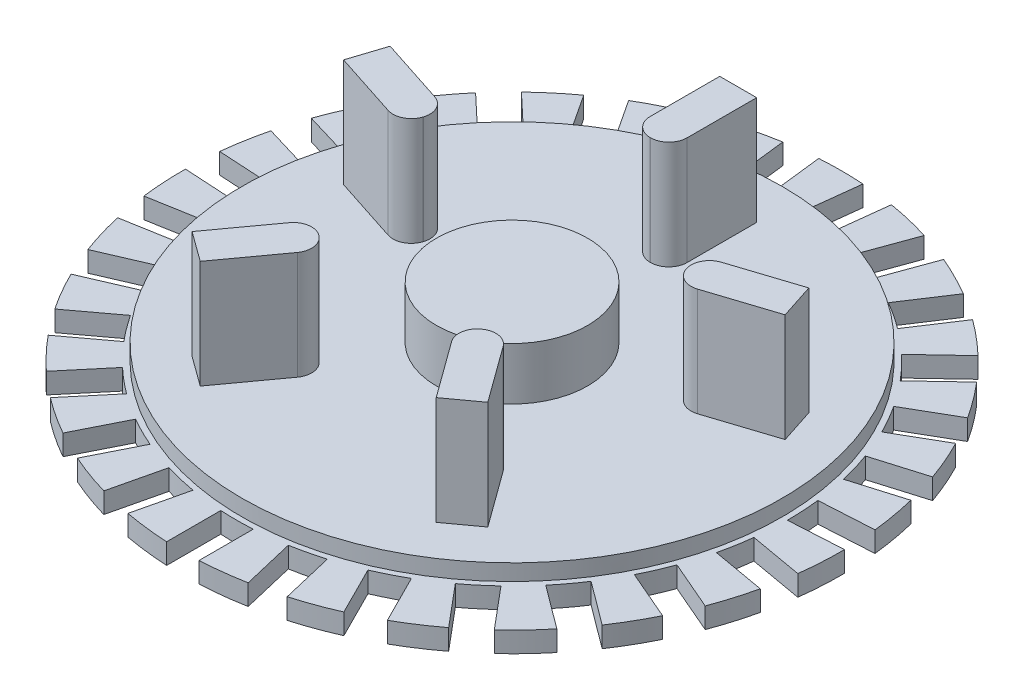
SolidWorks part; units mm, degrees
ref_plane "Front Plane" through (0, 0, 0) normal (0, 0, 1) x (1, 0, 0)
ref_plane "Top Plane" through (0, 0, 0) normal (0, 1, 0) x (1, 0, 0)
ref_plane "Right Plane" through (0, 0, 0) normal (1, 0, 0) x (0, 0, -1)
sketch "Sketch1" plane through (0, 0, 0) normal (0, 1, 0) x (1, 0, 0)
  circle A0 centre (0, 0) radius 25
  dimension "D1" = 50
extrude "Boss-Extrude1" add sketch "Sketch1" along normal blind 1.5
sketch "Sketch2" plane through (0, 1.5, 0) normal (0, 1, 0) x (1, 0, 0)
  line L0 (-1.7088, 14.5) -> (-1.7088, 19.3)
  line L1 (-0.0088, 12.8) -> (0.0088, 12.8)
  line L2 (-1.7088, 20.9304) -> (1.7088, 12.8) construction
  line L3 (1.7088, 14.5) -> (1.7088, 19.3)
  line L4 (-1.7088, 12.8) -> (1.7088, 20.9304) construction
  line L5 (0, -0.825) -> (0, 0.825) construction
  line L6 (-1.7088, 19.3) -> (-1.7088, 20.9304)
  line L7 (-1.7088, 20.9304) -> (1.7088, 20.9304)
  line L8 (1.7088, 20.9304) -> (1.7088, 19.3)
  arc A0 (0.0096, 21) -> (-0.0096, 21) centre (0, 0) ccw construction
  arc A1 (-1.7088, 19.3) -> (-0.0096, 21) centre (-0.0088, 19.3) cw construction
  arc A2 (1.7088, 19.3) -> (0.0096, 21) centre (0.0088, 19.3) ccw construction
  arc A3 (1.7088, 14.5) -> (0.0088, 12.8) centre (0.0088, 14.5) cw
  arc A4 (-1.7088, 14.5) -> (-0.0088, 12.8) centre (-0.0088, 14.5) ccw
  point P1 (0, 16.8652)
  point P3 (0, 21)
  dimension "D1" = 42
  dimension "D2" = 1.7
  dimension "D4" = 1.7
  dimension "D6" = 1.7
  dimension "D3" = 3.4176
  dimension "D5" = 6.5
extrude "Boss-Extrude2" add sketch "Sketch2" along normal blind 10
pattern_circular "CirPattern1" count 5 over 360 about axis through (0, 0, 0) along (0, 1, 0) of "Boss-Extrude2"
sketch "Sketch3" plane through (0, 0, 0) normal (0, -1, 0) x (1, 0, 0)
  circle A0 centre (0, 0) radius 30.5
  dimension "D1" = 61
extrude "Boss-Extrude3" add sketch "Sketch3" along normal blind 1.9
sketch "Sketch4" plane through (0, -1.9, 0) normal (0, -1, 0) x (1, 0, 0)
  line L0 (-1.5, 30.9637) -> (-1.5, 25.4558)
  line L1 (5.6812, 30.475) -> (4.411, 25.1156)
  line L2 (8.6003, 29.7831) -> (7.3301, 24.4238)
  line L3 (1.5, 30.9637) -> (1.5, 25.4558)
  line L4 (-1.4809, 30.9646) -> (1.5, 25.4558) construction
  line L5 (-1.5, 25.4558) -> (1.4809, 30.9646) construction
  line L6 (0, -6.325) -> (0, 6.325) construction
  line L7 (5.7, 30.4715) -> (7.3301, 24.4238) construction
  line L8 (4.411, 25.1156) -> (8.5819, 29.7884) construction
  line L9 (12.556, 28.3434) -> (10.0841, 23.4214)
  line L10 (15.2369, 26.997) -> (12.765, 22.075)
  line L11 (12.5736, 28.3356) -> (12.765, 22.075) construction
  line L12 (10.0841, 23.4214) -> (15.2202, 27.0064) construction
  line L13 (18.754, 24.6837) -> (15.2136, 20.4645)
  line L14 (21.0521, 22.7554) -> (17.5118, 18.5361)
  line L15 (18.7693, 24.6721) -> (17.5118, 18.5361) construction
  line L16 (15.2136, 20.4645) -> (21.0381, 22.7684) construction
  line L17 (23.941, 19.6934) -> (19.523, 16.4044)
  line L18 (25.7324, 17.287) -> (21.3145, 13.998)
  line L19 (23.9531, 19.6786) -> (21.3145, 13.998) construction
  line L20 (19.523, 16.4044) -> (25.7217, 17.303) construction
  line L21 (27.8372, 13.6414) -> (22.7798, 11.4599)
  line L22 (29.0255, 10.8868) -> (23.9681, 8.7052)
  line L23 (27.8457, 13.6242) -> (23.9681, 8.7052) construction
  line L24 (22.7798, 11.4599) -> (29.0187, 10.9047) construction
  line L25 (30.2328, 6.854) -> (24.8086, 5.8976)
  line L26 (30.7538, 3.8996) -> (25.3296, 2.9431)
  line L27 (30.237, 6.8353) -> (25.3296, 2.9431) construction
  line L28 (24.8086, 5.8976) -> (30.7513, 3.9186) construction
  line L29 (30.9985, -0.3029) -> (25.5, 0.0173)
  line L30 (30.8241, -3.2978) -> (25.3256, -2.9776)
  line L31 (30.9983, -0.3221) -> (25.3256, -2.9776) construction
  line L32 (25.5, 0.0173) -> (30.8261, -3.2788) construction
  line L33 (30.0931, -7.4435) -> (24.8166, -5.8638)
  line L34 (29.2327, -10.3175) -> (23.9562, -8.7378)
  line L35 (30.0885, -7.4621) -> (23.9562, -8.7378) construction
  line L36 (24.8166, -5.8638) -> (29.2391, -10.2994) construction
  line L37 (27.5653, -14.1828) -> (22.7954, -11.4289)
  line L38 (26.0653, -16.7809) -> (21.2954, -14.027)
  line L39 (27.5566, -14.1999) -> (21.2954, -14.027) construction
  line L40 (22.7954, -11.4289) -> (26.0757, -16.7648) construction
  line L41 (23.5515, -20.1575) -> (19.5453, -16.3778)
  line L42 (21.4928, -22.3396) -> (17.4865, -18.5599)
  line L43 (23.5391, -20.1721) -> (17.4865, -18.5599) construction
  line L44 (19.5453, -16.3778) -> (21.5066, -22.3263) construction
  line L45 (18.2681, -25.0455) -> (15.2414, -20.4438)
  line L46 (15.7616, -26.694) -> (12.735, -22.0923)
  line L47 (18.2526, -25.0568) -> (12.735, -22.0923) construction
  line L48 (15.2414, -20.4438) -> (15.7781, -26.6843) construction
  line L49 (11.9997, -28.5833) -> (10.116, -23.4076)
  line L50 (9.1807, -29.6094) -> (7.2969, -24.4337)
  line L51 (11.9821, -28.5907) -> (7.2969, -24.4337) construction
  line L52 (10.116, -23.4076) -> (9.199, -29.6037) construction
  line L53 (5.0845, -30.5802) -> (4.4451, -25.1096)
  line L54 (2.1048, -30.9285) -> (1.4654, -25.4579)
  line L55 (5.0656, -30.5833) -> (1.4654, -25.4579) construction
  line L56 (4.4451, -25.1096) -> (2.1239, -30.9272) construction
  line L57 (-2.1048, -30.9285) -> (-1.4654, -25.4579)
  line L58 (-5.0845, -30.5802) -> (-4.4451, -25.1096)
  line L59 (-2.1239, -30.9272) -> (-4.4451, -25.1096) construction
  line L60 (-1.4654, -25.4579) -> (-5.0656, -30.5833) construction
  line L61 (-9.1807, -29.6094) -> (-7.2969, -24.4337)
  line L62 (-11.9997, -28.5833) -> (-10.116, -23.4076)
  line L63 (-9.199, -29.6037) -> (-10.116, -23.4076) construction
  line L64 (-7.2969, -24.4337) -> (-11.9821, -28.5907) construction
  line L65 (-15.7616, -26.694) -> (-12.735, -22.0923)
  line L66 (-18.2681, -25.0455) -> (-15.2414, -20.4438)
  line L67 (-15.7781, -26.6843) -> (-15.2414, -20.4438) construction
  line L68 (-12.735, -22.0923) -> (-18.2526, -25.0568) construction
  line L69 (-21.4928, -22.3396) -> (-17.4865, -18.5599)
  line L70 (-23.5515, -20.1575) -> (-19.5453, -16.3778)
  line L71 (-21.5066, -22.3263) -> (-19.5453, -16.3778) construction
  line L72 (-17.4865, -18.5599) -> (-23.5391, -20.1721) construction
  line L73 (-26.0653, -16.7809) -> (-21.2954, -14.027)
  line L74 (-27.5653, -14.1828) -> (-22.7954, -11.4289)
  line L75 (-26.0757, -16.7648) -> (-22.7954, -11.4289) construction
  line L76 (-21.2954, -14.027) -> (-27.5566, -14.1999) construction
  line L77 (-29.2327, -10.3175) -> (-23.9562, -8.7378)
  line L78 (-30.0931, -7.4435) -> (-24.8166, -5.8638)
  line L79 (-29.2391, -10.2994) -> (-24.8166, -5.8638) construction
  line L80 (-23.9562, -8.7378) -> (-30.0885, -7.4621) construction
  line L81 (-30.8241, -3.2978) -> (-25.3256, -2.9776)
  line L82 (-30.9985, -0.3029) -> (-25.5, 0.0173)
  line L83 (-30.8261, -3.2788) -> (-25.5, 0.0173) construction
  line L84 (-25.3256, -2.9776) -> (-30.9983, -0.3221) construction
  line L85 (-30.7538, 3.8996) -> (-25.3296, 2.9431)
  line L86 (-30.2328, 6.854) -> (-24.8086, 5.8976)
  line L87 (-30.7513, 3.9186) -> (-24.8086, 5.8976) construction
  line L88 (-25.3296, 2.9431) -> (-30.237, 6.8353) construction
  line L89 (-29.0255, 10.8868) -> (-23.9681, 8.7052)
  line L90 (-27.8372, 13.6414) -> (-22.7798, 11.4599)
  line L91 (-29.0187, 10.9047) -> (-22.7798, 11.4599) construction
  line L92 (-23.9681, 8.7052) -> (-27.8457, 13.6242) construction
  line L93 (-25.7324, 17.287) -> (-21.3145, 13.998)
  line L94 (-23.941, 19.6934) -> (-19.523, 16.4044)
  line L95 (-25.7217, 17.303) -> (-19.523, 16.4044) construction
  line L96 (-21.3145, 13.998) -> (-23.9531, 19.6786) construction
  line L97 (-21.0521, 22.7554) -> (-17.5118, 18.5361)
  line L98 (-18.754, 24.6837) -> (-15.2136, 20.4645)
  line L99 (-21.0381, 22.7684) -> (-15.2136, 20.4645) construction
  line L100 (-17.5118, 18.5361) -> (-18.7693, 24.6721) construction
  line L101 (-15.2369, 26.997) -> (-12.765, 22.075)
  line L102 (-12.556, 28.3434) -> (-10.0841, 23.4214)
  line L103 (-15.2202, 27.0064) -> (-10.0841, 23.4214) construction
  line L104 (-12.765, 22.075) -> (-12.5736, 28.3356) construction
  line L105 (-8.6003, 29.7831) -> (-7.3301, 24.4238)
  line L106 (-5.6812, 30.475) -> (-4.411, 25.1156)
  line L107 (-8.5819, 29.7884) -> (-4.411, 25.1156) construction
  line L108 (-7.3301, 24.4238) -> (-5.7, 30.4715) construction
  arc A0 (1.5, 30.9637) -> (-1.5, 30.9637) centre (0, 0) ccw
  arc A1 (1.5, 25.4558) -> (-1.5, 25.4558) centre (0, 0) ccw
  arc A2 (8.6003, 29.7831) -> (5.6812, 30.475) centre (0, 0) ccw
  arc A3 (7.3301, 24.4238) -> (4.411, 25.1156) centre (0, 0) ccw
  arc A4 (15.2369, 26.997) -> (12.556, 28.3434) centre (0, 0) ccw
  arc A5 (12.765, 22.075) -> (10.0841, 23.4214) centre (0, 0) ccw
  arc A6 (21.0521, 22.7554) -> (18.754, 24.6837) centre (0, 0) ccw
  arc A7 (17.5118, 18.5361) -> (15.2136, 20.4645) centre (0, 0) ccw
  arc A8 (25.7324, 17.287) -> (23.941, 19.6934) centre (0, 0) ccw
  arc A9 (21.3145, 13.998) -> (19.523, 16.4044) centre (0, 0) ccw
  arc A10 (29.0255, 10.8868) -> (27.8372, 13.6414) centre (0, 0) ccw
  arc A11 (23.9681, 8.7052) -> (22.7798, 11.4599) centre (0, 0) ccw
  arc A12 (30.7538, 3.8996) -> (30.2328, 6.854) centre (0, 0) ccw
  arc A13 (25.3296, 2.9431) -> (24.8086, 5.8976) centre (0, 0) ccw
  arc A14 (30.8241, -3.2978) -> (30.9985, -0.3029) centre (0, 0) ccw
  arc A15 (25.3256, -2.9776) -> (25.5, 0.0173) centre (0, 0) ccw
  arc A16 (29.2327, -10.3175) -> (30.0931, -7.4435) centre (0, 0) ccw
  arc A17 (23.9562, -8.7378) -> (24.8166, -5.8638) centre (0, 0) ccw
  arc A18 (26.0653, -16.7809) -> (27.5653, -14.1828) centre (0, 0) ccw
  arc A19 (21.2954, -14.027) -> (22.7954, -11.4289) centre (0, 0) ccw
  arc A20 (21.4928, -22.3396) -> (23.5515, -20.1575) centre (0, 0) ccw
  arc A21 (17.4865, -18.5599) -> (19.5453, -16.3778) centre (0, 0) ccw
  arc A22 (15.7616, -26.694) -> (18.2681, -25.0455) centre (0, 0) ccw
  arc A23 (12.735, -22.0923) -> (15.2414, -20.4438) centre (0, 0) ccw
  arc A24 (9.1807, -29.6094) -> (11.9997, -28.5833) centre (0, 0) ccw
  arc A25 (7.2969, -24.4337) -> (10.116, -23.4076) centre (0, 0) ccw
  arc A26 (2.1048, -30.9285) -> (5.0845, -30.5802) centre (0, 0) ccw
  arc A27 (1.4654, -25.4579) -> (4.4451, -25.1096) centre (0, 0) ccw
  arc A28 (-5.0845, -30.5802) -> (-2.1048, -30.9285) centre (0, 0) ccw
  arc A29 (-4.4451, -25.1096) -> (-1.4654, -25.4579) centre (0, 0) ccw
  arc A30 (-11.9997, -28.5833) -> (-9.1807, -29.6094) centre (0, 0) ccw
  arc A31 (-10.116, -23.4076) -> (-7.2969, -24.4337) centre (0, 0) ccw
  arc A32 (-18.2681, -25.0455) -> (-15.7616, -26.694) centre (0, 0) ccw
  arc A33 (-15.2414, -20.4438) -> (-12.735, -22.0923) centre (0, 0) ccw
  arc A34 (-23.5515, -20.1575) -> (-21.4928, -22.3396) centre (0, 0) ccw
  arc A35 (-19.5453, -16.3778) -> (-17.4865, -18.5599) centre (0, 0) ccw
  arc A36 (-27.5653, -14.1828) -> (-26.0653, -16.7809) centre (0, 0) ccw
  arc A37 (-22.7954, -11.4289) -> (-21.2954, -14.027) centre (0, 0) ccw
  arc A38 (-30.0931, -7.4435) -> (-29.2327, -10.3175) centre (0, 0) ccw
  arc A39 (-24.8166, -5.8638) -> (-23.9562, -8.7378) centre (0, 0) ccw
  arc A40 (-30.9985, -0.3029) -> (-30.8241, -3.2978) centre (0, 0) ccw
  arc A41 (-25.5, 0.0173) -> (-25.3256, -2.9776) centre (0, 0) ccw
  arc A42 (-30.2328, 6.854) -> (-30.7538, 3.8996) centre (0, 0) ccw
  arc A43 (-24.8086, 5.8976) -> (-25.3296, 2.9431) centre (0, 0) ccw
  arc A44 (-27.8372, 13.6414) -> (-29.0255, 10.8868) centre (0, 0) ccw
  arc A45 (-22.7798, 11.4599) -> (-23.9681, 8.7052) centre (0, 0) ccw
  arc A46 (-23.941, 19.6934) -> (-25.7324, 17.287) centre (0, 0) ccw
  arc A47 (-19.523, 16.4044) -> (-21.3145, 13.998) centre (0, 0) ccw
  arc A48 (-18.754, 24.6837) -> (-21.0521, 22.7554) centre (0, 0) ccw
  arc A49 (-15.2136, 20.4645) -> (-17.5118, 18.5361) centre (0, 0) ccw
  arc A50 (-12.556, 28.3434) -> (-15.2369, 26.997) centre (0, 0) ccw
  arc A51 (-10.0841, 23.4214) -> (-12.765, 22.075) centre (0, 0) ccw
  arc A52 (-5.6812, 30.475) -> (-8.6003, 29.7831) centre (0, 0) ccw
  arc A53 (-4.411, 25.1156) -> (-7.3301, 24.4238) centre (0, 0) ccw
  point P4 (0, 31)
  point P5 (0, 28.2279)
  point P17 (7.1491, 30.1644)
  point P18 (6.5098, 27.467)
  point P25 (13.9128, 27.7026)
  point P26 (12.6687, 25.2254)
  point P33 (19.9264, 23.7474)
  point P34 (18.1446, 21.6238)
  point P41 (24.8658, 18.5119)
  point P42 (22.6423, 16.8565)
  point P49 (28.4647, 12.2785)
  point P50 (25.9193, 11.1805)
  point P57 (30.529, 5.3831)
  point P58 (27.7991, 4.9017)
  point P65 (30.9476, -1.8025)
  point P66 (28.1802, -1.6413)
  point P73 (29.6977, -8.8909)
  point P74 (27.0421, -8.0959)
  point P81 (26.8468, -15.5)
  point P82 (24.4461, -14.114)
  point P89 (22.5486, -21.2735)
  point P90 (20.5322, -19.3712)
  point P97 (17.0348, -25.9001)
  point P98 (15.5115, -23.5841)
  point P105 (10.6026, -29.1305)
  point P106 (9.6545, -26.5256)
  point P113 (3.5989, -30.7904)
  point P114 (3.2771, -28.0371)
  point P121 (-3.5989, -30.7904)
  point P122 (-3.2771, -28.0371)
  point P129 (-10.6026, -29.1305)
  point P130 (-9.6545, -26.5256)
  point P137 (-17.0348, -25.9001)
  point P138 (-15.5115, -23.5841)
  point P145 (-22.5486, -21.2735)
  point P146 (-20.5322, -19.3712)
  point P153 (-26.8468, -15.5)
  point P154 (-24.4461, -14.114)
  point P161 (-29.6977, -8.8909)
  point P162 (-27.0421, -8.0959)
  point P169 (-30.9476, -1.8025)
  point P170 (-28.1802, -1.6413)
  point P177 (-30.529, 5.3831)
  point P178 (-27.7991, 4.9017)
  point P185 (-28.4647, 12.2785)
  point P186 (-25.9193, 11.1805)
  point P193 (-24.8658, 18.5119)
  point P194 (-22.6423, 16.8565)
  point P201 (-19.9264, 23.7474)
  point P202 (-18.1446, 21.6238)
  point P209 (-13.9128, 27.7026)
  point P210 (-12.6687, 25.2254)
  point P217 (-7.1491, 30.1644)
  point P218 (-6.5098, 27.467)
  point P223 (0, 0)
  dimension "D1" = 62
  dimension "D2" = 51
  dimension "D3" = 3
  dimension "D4" = 27
extrude "Cut-Extrude2" cut sketch "Sketch4" against normal through all
sketch "Sketch5" plane through (0, 1.5, 0) normal (0, 1, 0) x (1, 0, 0)
  circle A0 centre (0, 0) radius 7
  dimension "D1" = 14
extrude "Boss-Extrude4" add sketch "Sketch5" along normal blind 4.85
